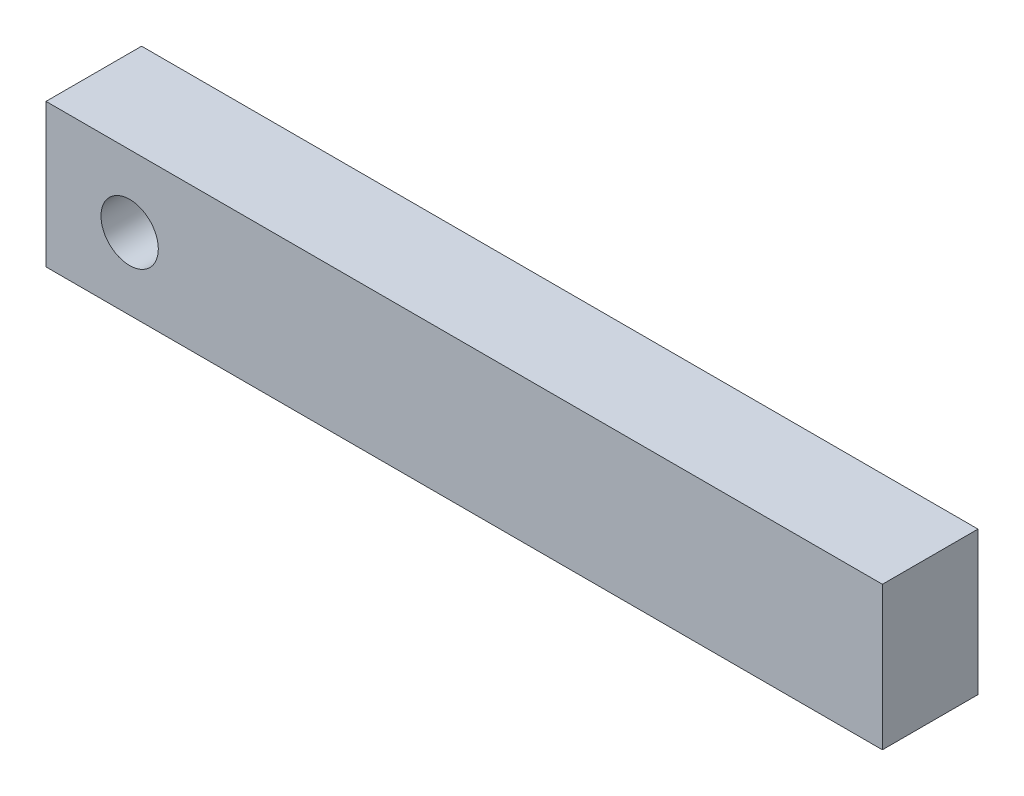
SolidWorks part; units mm, degrees
material "6061-T6 (SS)"
ref_plane "前视基准面" through (0, 0, 0) normal (0, 0, 1) x (1, 0, 0)
ref_plane "上视基准面" through (0, 0, 0) normal (0, 1, 0) x (1, 0, 0)
ref_plane "右视基准面" through (0, 0, 0) normal (1, 0, 0) x (0, 0, -1)
other "Configuration Table"
sketch "草图8" plane through (0, 0, 0) normal (0, 0, 1) x (1, 0, 0)
  line L1 (-175, 30) -> (175, 30)
  line L2 (-175, 30) -> (-175, -30)
  line L3 (-175, -30) -> (175, -30)
  line L4 (175, 30) -> (175, -30)
extrude "凸台-拉伸1" add sketch "草图8" along normal blind 40
sketch "草图9" plane through (0, 0, 40) normal (0, 0, 1) x (1, 0, 0)
  circle A0 centre (-140, 0) radius 12
extrude "切除-拉伸1" cut sketch "草图9" against normal through all
